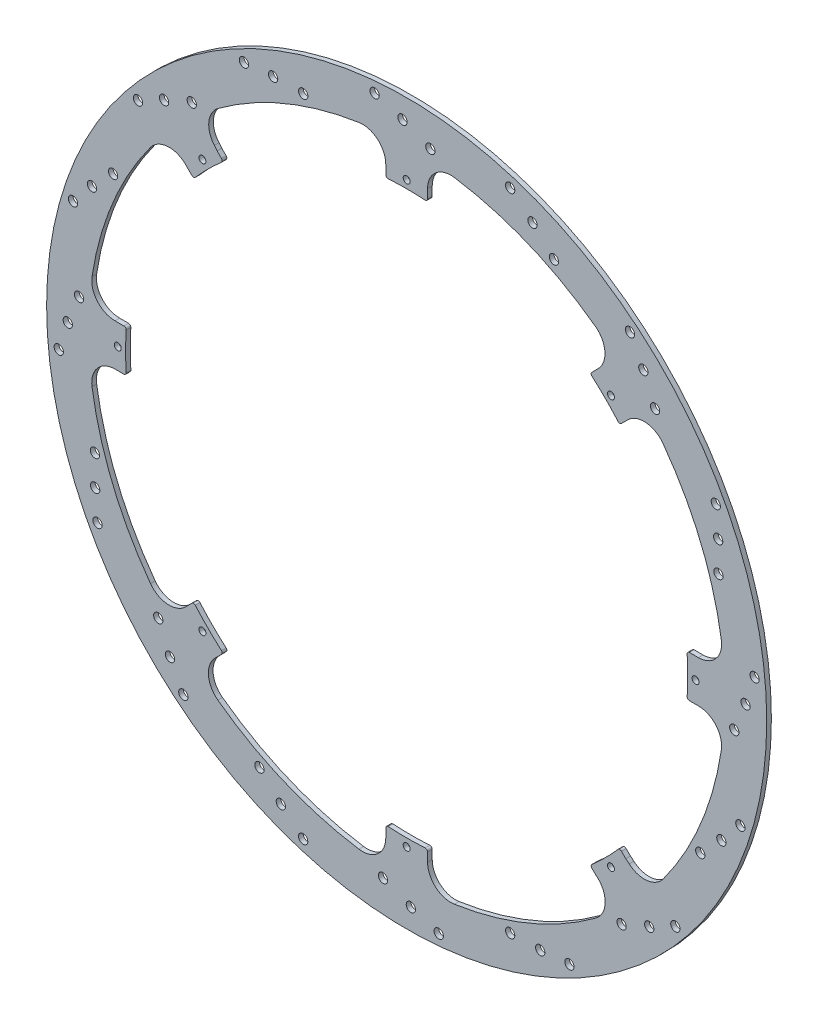
SolidWorks part; units mm, degrees
ref_plane "Ön Düzlem" through (0, 0, 0) normal (0, 0, 1) x (1, 0, 0)
ref_plane "Üst Düzlem" through (0, 0, 0) normal (0, 1, 0) x (1, 0, 0)
ref_plane "Sağ Düzlem" through (0, 0, 0) normal (1, 0, 0) x (0, 0, -1)
sketch "Çizim1" plane through (0, 0, 0) normal (0, 0, 1) x (1, 0, 0)
  circle A0 centre (0, 0) radius 155
  circle A1 centre (0, 0) radius 124
  dimension "D1" = 310
  dimension "D2" = 248
extrude "Yükseklik-Ekstrüzyon1" add sketch "Çizim1" along normal blind 2
sketch "Çizim2" plane through (0, 0, 2) normal (0, 0, 1) x (1, 0, 0)
  line L0 (9, -123.673) -> (9, -136.7041)
  line L1 (81.086, -93.8139) -> (91.016, -102.3967)
  line L2 (93.8139, -81.086) -> (103.6493, -89.587)
  line L3 (-9, -123.673) -> (-9, -136.7041)
  line L4 (-93.8139, 81.086) -> (-103.0283, 90.3004)
  line L5 (-81.086, 93.8139) -> (-89.587, 103.6493)
  line L6 (9, 136.7041) -> (9, 123.673)
  line L7 (-9, 123.673) -> (-9, 136.7041)
  line L8 (-136.7041, 9) -> (-123.673, 9)
  line L9 (-93.8139, -81.086) -> (-103.0283, -90.3004)
  line L11 (-81.086, -93.8139) -> (-90.3004, -103.0283)
  line L12 (81.086, 93.8139) -> (90.3004, 103.0283)
  line L13 (93.8139, 81.086) -> (103.0283, 90.3004)
  line L14 (136.7041, -9) -> (123.673, -9)
  line L15 (123.673, 9) -> (136.7041, 9)
  line L16 (-123.673, -9) -> (-136.7041, -9)
  circle A0 centre (0, 0) radius 124 construction
  arc A1 (-9, 123.673) -> (9, 123.673) centre (0, 0) cw
  arc A2 (81.086, 93.8139) -> (93.8139, 81.086) centre (0, 0) cw
  arc A3 (123.673, 9) -> (123.673, -9) centre (0, 0) cw
  arc A4 (93.8139, -81.086) -> (81.086, -93.8139) centre (0, 0) cw
  arc A5 (9, -123.673) -> (-9, -123.673) centre (0, 0) cw
  arc A6 (-81.086, -93.8139) -> (-93.8139, -81.086) centre (0, 0) cw
  arc A7 (-123.673, -9) -> (-123.673, 9) centre (0, 0) cw
  arc A8 (-93.8139, 81.086) -> (-81.086, 93.8139) centre (0, 0) cw
  circle A9 centre (0, 0) radius 137
  circle A10 centre (0, 0) radius 124
  point P24 (0, 0)
  circle M10 centre (0, 0) radius 124
  dimension "D4" = 274
  dimension "D3" = 8
extrude "Kes-Ekstrüzyon1" cut sketch "Çizim2" against normal blind 52 contours L7 A9 L5 M10 | L12 A9 L6 M10 | L15 A9 L13 M10 | L2 A9 L14 M10 | L0 A9 L1 M10 | L11 A9 L3 M10 | L16 A9 L9 M10 | L4 A9 L8 M10 | A10
fillet "Radyus1" radius 10 16 edges at (-136.7041, -9, 1) (-136.7041, 9, 1) (-103.0283, 90.3004, 1) (-103.0283, -90.3004, 1) (-90.3004, -103.0283, 1) (-9, -136.7041, 1) (9, -136.7041, 1) (91.016, -102.3967, 1) (103.6493, -89.587, 1) (136.7041, -9, 1) (136.7041, 9, 1) (103.0283, 90.3004, 1) (90.3004, 103.0283, 1) (9, 136.7041, 1) (-9, 136.7041, 1) (-89.587, 103.6493, 1)
sketch "Çizim4" plane through (0, 0, 2) normal (0, 0, 1) x (1, 0, 0)
  circle A3 centre (44.5614, 143.6376) radius 2
  circle A4 centre (54.1644, 135.4637) radius 2
  circle A6 centre (-13.7983, 149.7567) radius 2
  circle A7 centre (-1.7983, 145.88) radius 2
  circle A8 centre (10.2017, 141.0225) radius 2
  circle A9 centre (63.3921, 126.3838) radius 2
  circle A10 centre (96.1371, 115.6509) radius 2
  circle A11 centre (101.8811, 104.4243) radius 2
  circle A12 centre (106.9317, 92.5043) radius 2
  circle A13 centre (133.0768, 70.0574) radius 2
  circle A14 centre (134.0873, 57.4873) radius 2
  circle A15 centre (134.1919, 44.5419) radius 2
  circle A16 centre (149.7567, 13.7983) radius 2
  circle A17 centre (145.88, 1.7983) radius 2
  circle A18 centre (141.0225, -10.2017) radius 2
  circle A19 centre (143.6376, -44.5614) radius 2
  circle A20 centre (135.4637, -54.1644) radius 2
  circle A21 centre (126.3838, -63.3921) radius 2
  circle A22 centre (115.6509, -96.1371) radius 2
  circle A23 centre (104.4243, -101.8811) radius 2
  circle A24 centre (92.5043, -106.9317) radius 2
  circle A25 centre (70.0574, -133.0768) radius 2
  circle A26 centre (57.4873, -134.0873) radius 2
  circle A27 centre (44.5419, -134.1919) radius 2
  circle A28 centre (13.7983, -149.7567) radius 2
  circle A29 centre (1.7983, -145.88) radius 2
  circle A30 centre (-10.2017, -141.0225) radius 2
  circle A31 centre (-44.5614, -143.6376) radius 2
  circle A32 centre (-54.1644, -135.4637) radius 2
  circle A33 centre (-63.3921, -126.3838) radius 2
  circle A34 centre (-96.1371, -115.6509) radius 2
  circle A35 centre (-101.8811, -104.4243) radius 2
  circle A36 centre (-106.9317, -92.5043) radius 2
  circle A37 centre (-133.0768, -70.0574) radius 2
  circle A38 centre (-134.0873, -57.4873) radius 2
  circle A39 centre (-134.1919, -44.5419) radius 2
  circle A40 centre (-149.7567, -13.7983) radius 2
  circle A41 centre (-145.88, -1.7983) radius 2
  circle A42 centre (-141.0225, 10.2017) radius 2
  circle A43 centre (-143.6376, 44.5614) radius 2
  circle A44 centre (-135.4637, 54.1644) radius 2
  circle A45 centre (-126.3838, 63.3921) radius 2
  circle A46 centre (-115.6509, 96.1371) radius 2
  circle A47 centre (-104.4243, 101.8811) radius 2
  circle A48 centre (-92.5043, 106.9317) radius 2
  circle A49 centre (-70.0574, 133.0768) radius 2
  circle A50 centre (-57.4873, 134.0873) radius 2
  circle A51 centre (-44.5419, 134.1919) radius 2
  point P107 (0, 0)
  dimension "D4" = 4
  dimension "D5" = 4
  dimension "D6" = 4
  dimension "D7" = 12
  dimension "D8" = 12
  dimension "D9" = 16
extrude "Kes-Ekstrüzyon3" cut sketch "Çizim4" against normal blind 52
sketch "Çizim5" plane through (0, 0, 2) normal (0, 0, 1) x (1, 0, 0)
  circle A0 centre (0, 0) radius 124.709
extrude "Kes-Ekstrüzyon4" cut sketch "Çizim5" against normal blind 10
sketch "Çizim6" plane through (0, 0, 2) normal (0, 0, 1) x (1, 0, 0)
  line L0 (-9, 124.3838) -> (-9, 120.6648)
  line L1 (9, 124.3838) -> (9, 120.6648)
  line L2 (81.5887, 94.3166) -> (78.959, 91.6869)
  line L3 (94.3166, 81.5887) -> (91.6869, 78.959)
  line L4 (124.3838, 9) -> (120.6648, 9)
  line L5 (124.3838, -9) -> (120.6648, -9)
  line L6 (94.3166, -81.5887) -> (91.6869, -78.959)
  line L7 (81.5887, -94.3166) -> (78.959, -91.6869)
  line L8 (9, -124.3838) -> (9, -120.6648)
  line L9 (-9, -124.3838) -> (-9, -120.6648)
  line L10 (-81.5887, -94.3166) -> (-78.959, -91.6869)
  line L11 (-94.3166, -81.5887) -> (-91.6869, -78.959)
  line L12 (-124.3838, -9) -> (-120.6648, -9)
  line L13 (-124.3838, 9) -> (-120.6648, 9)
  line L14 (-94.3166, 81.5887) -> (-91.6869, 78.959)
  line L15 (-81.5887, 94.3166) -> (-78.959, 91.6869)
  arc A0 (9, 120.6648) -> (-9, 120.6648) centre (0, 0) ccw
  arc A1 (9, 124.3838) -> (-9, 124.3838) centre (0, 0) ccw
  arc A2 (94.3166, 81.5887) -> (81.5887, 94.3166) centre (0, 0) ccw
  arc A3 (91.6869, 78.959) -> (78.959, 91.6869) centre (0, 0) ccw
  arc A4 (124.3838, -9) -> (124.3838, 9) centre (0, 0) ccw
  arc A5 (120.6648, -9) -> (120.6648, 9) centre (0, 0) ccw
  arc A6 (81.5887, -94.3166) -> (94.3166, -81.5887) centre (0, 0) ccw
  arc A7 (78.959, -91.6869) -> (91.6869, -78.959) centre (0, 0) ccw
  arc A8 (-9, -124.3838) -> (9, -124.3838) centre (0, 0) ccw
  arc A9 (-9, -120.6648) -> (9, -120.6648) centre (0, 0) ccw
  arc A10 (-94.3166, -81.5887) -> (-81.5887, -94.3166) centre (0, 0) ccw
  arc A11 (-91.6869, -78.959) -> (-78.959, -91.6869) centre (0, 0) ccw
  arc A12 (-124.3838, 9) -> (-124.3838, -9) centre (0, 0) ccw
  arc A13 (-120.6648, 9) -> (-120.6648, -9) centre (0, 0) ccw
  arc A14 (-81.5887, 94.3166) -> (-94.3166, 81.5887) centre (0, 0) ccw
  arc A15 (-78.959, 91.6869) -> (-91.6869, 78.959) centre (0, 0) ccw
  point P40 (0, 0)
  dimension "D1" = 242
  dimension "D2" = 8
extrude "Yükseklik-Ekstrüzyon3" add sketch "Çizim6" against normal up to surface (2 mm away) up to face at (-42.5419, 134.1919, 0)
sketch "Çizim7" plane through (0, 0, 2) normal (0, 0, 1) x (1, 0, 0)
  circle A0 centre (0, 124.364) radius 1.5
  circle A1 centre (87.9387, 87.9387) radius 1.5
  circle A2 centre (124.364, 0) radius 1.5
  circle A3 centre (87.9387, -87.9387) radius 1.5
  circle A4 centre (0, -124.364) radius 1.5
  circle A5 centre (-87.9387, -87.9387) radius 1.5
  circle A6 centre (-124.364, 0) radius 1.5
  circle A7 centre (-87.9387, 87.9387) radius 1.5
  point P18 (0, 0)
  dimension "D1" = 3
  dimension "D2" = 8
extrude "Kes-Ekstrüzyon5" cut sketch "Çizim7" against normal blind 36
fillet "Radyus2" radius 1 16 edges at (91.6869, 78.959, 1) (78.959, 91.6869, 1) (120.6648, -9, 1) (120.6648, 9, 1) (91.6869, -78.959, 1) (78.959, -91.6869, 1) (-9, -120.6648, 1) (9, -120.6648, 1) (-91.6869, -78.959, 1) (-78.959, -91.6869, 1) (-120.6648, 9, 1) (-120.6648, -9, 1) (-91.6869, 78.959, 1) (-78.959, 91.6869, 1) (-9, 120.6648, 1) (9, 120.6648, 1)
